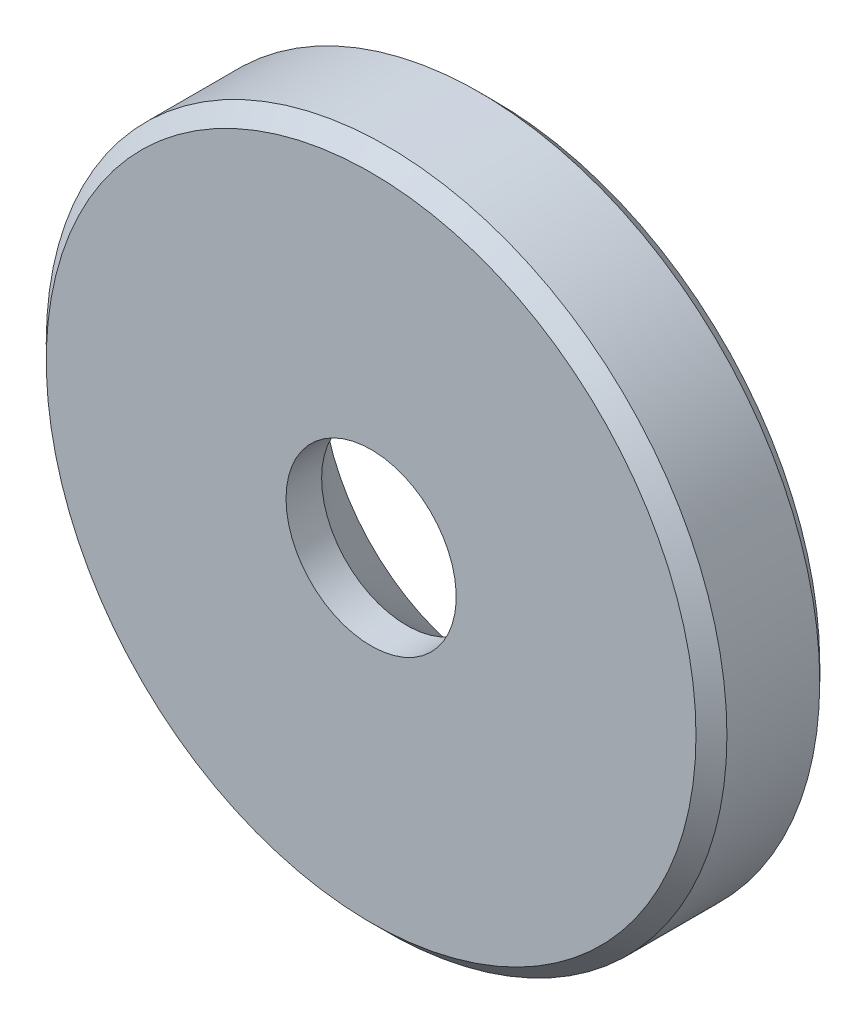
SolidWorks part; units mm, degrees
material "2A12"
ref_plane "前视基准面" through (0, 0, 0) normal (0, 0, 1) x (1, 0, 0)
ref_plane "上视基准面" through (0, 0, 0) normal (0, 1, 0) x (1, 0, 0)
ref_plane "右视基准面" through (0, 0, 0) normal (1, 0, 0) x (0, 0, -1)
sketch "草图1" plane through (0, 0, 0) normal (0, 0, 1) x (1, 0, 0)
  circle A0 centre (0, 0) radius 11
  dimension "D1" = 22
extrude "拉伸1" add sketch "草图1" along normal blind 4
chamfer "倒角1" distance 0.5 angle 45 2 edges at (11, 0, 0) (11, 0, 4)
hole_wizard "打孔尺寸根据十字槽沉头木螺钉的类型1" positions "3D草图1" profile "草图2" countersink size "M5" standard "GB" end condition through all
sketch3d "3D草图1"
  point P0 (0, 0, 0)
sketch "草图2" plane through (0, 0, 0) normal (1, 0, 0) x (0, 1, 0)
  line L0 (0, 0) -> (0, 4)
  line L1 (0, 4) -> (2.75, 4)
  line L2 (2.75, 4) -> (2.75, 2.85)
  line L3 (2.75, 2.85) -> (5.6, 0)
  line L5 (5.6, 0) -> (0, 0)
  line L6 (-2.75, 2.85) -> (-5.6, 0) construction
  line L11 (0, -6.35) -> (0, 107.95) construction
  dimension "通孔孔直径" = 5.5
  dimension "通孔孔深度" = 4
  dimension "近端锥形沉头孔直径" = 11.2
  dimension "近端锥形沉头孔角度" = 90
